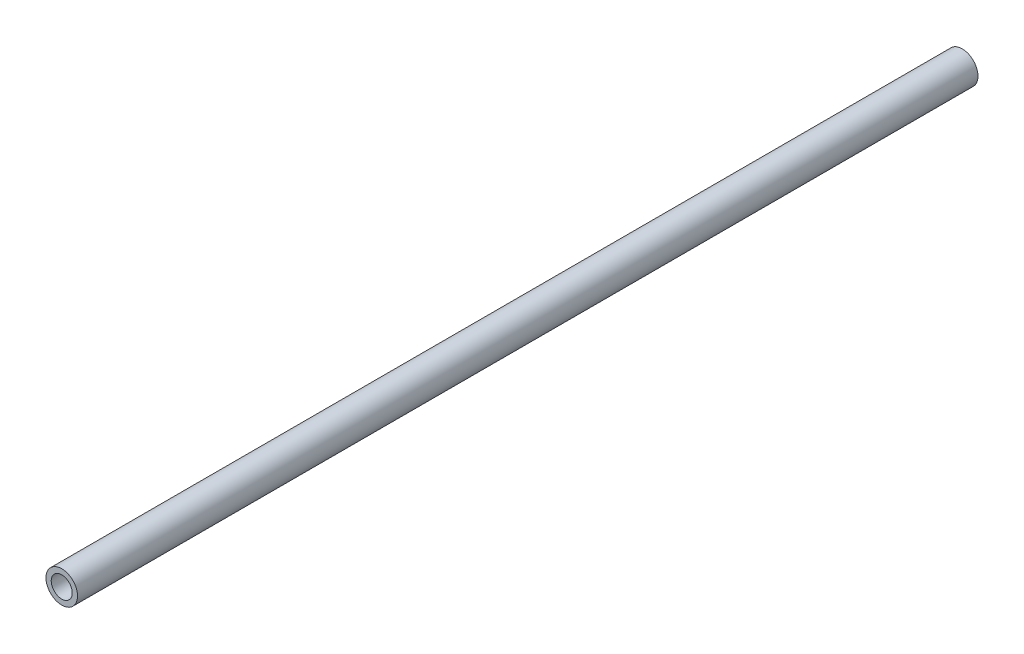
SolidWorks part; units mm, degrees
material "3003-H16"
ref_plane "Front Plane" through (0, 0, 0) normal (0, 0, 1) x (1, 0, 0)
ref_plane "Top Plane" through (0, 0, 0) normal (0, 1, 0) x (1, 0, 0)
ref_plane "Right Plane" through (0, 0, 0) normal (1, 0, 0) x (0, 0, -1)
sketch "Sketch1" plane through (0, 0, 0) normal (0, 0, 1) x (1, 0, 0)
  circle A0 centre (0, 0) radius 9.525
  circle A1 centre (0, 0) radius 6.35
  dimension "D1" = 19.05
  dimension "D2" = 12.7
extrude "Boss-Extrude1" add sketch "Sketch1" against normal blind 543.75
